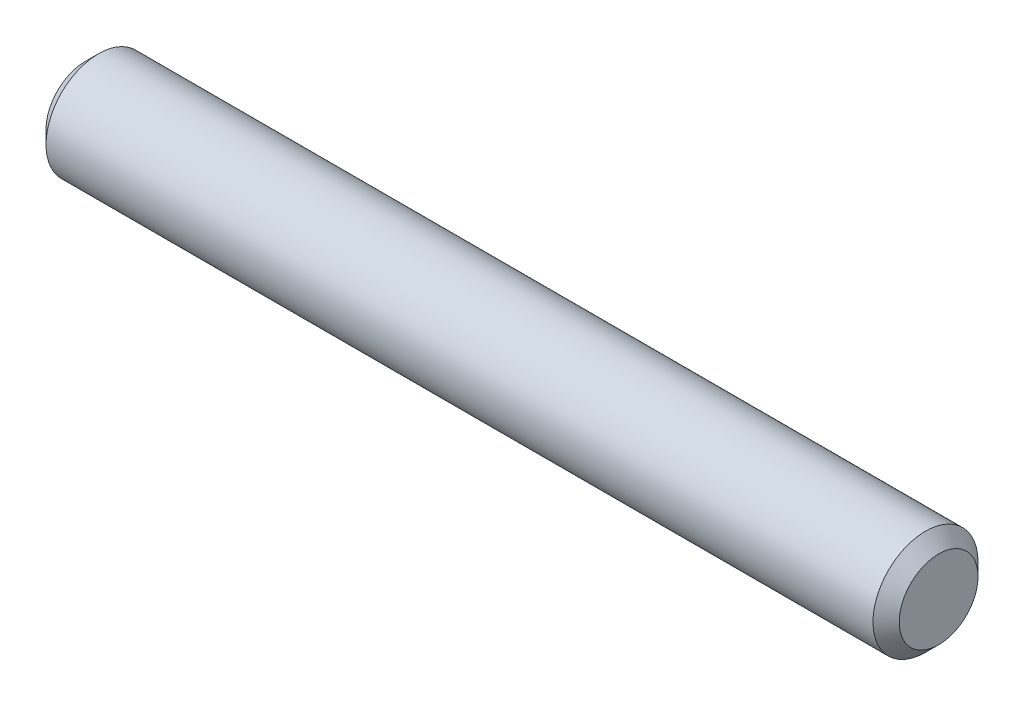
SolidWorks part; units mm, degrees
ref_plane "Front Plane" through (0, 0, 0) normal (0, 0, 1) x (1, 0, 0)
ref_plane "Top Plane" through (0, 0, 0) normal (0, 1, 0) x (1, 0, 0)
ref_plane "Right Plane" through (0, 0, 0) normal (1, 0, 0) x (0, 0, -1)
sketch "Sketch1" plane through (0, 0, 0) normal (1, 0, 0) x (0, 0, -1)
  circle A0 centre (0, 0.3764) radius 4
  dimension "D1" = 8
extrude "Boss-Extrude1" add sketch "Sketch1" along normal blind 65
chamfer "Chamfer1" distance 1 angle 45 2 edges at (0, 0.3764, -4) (65, 0.3764, -4)
